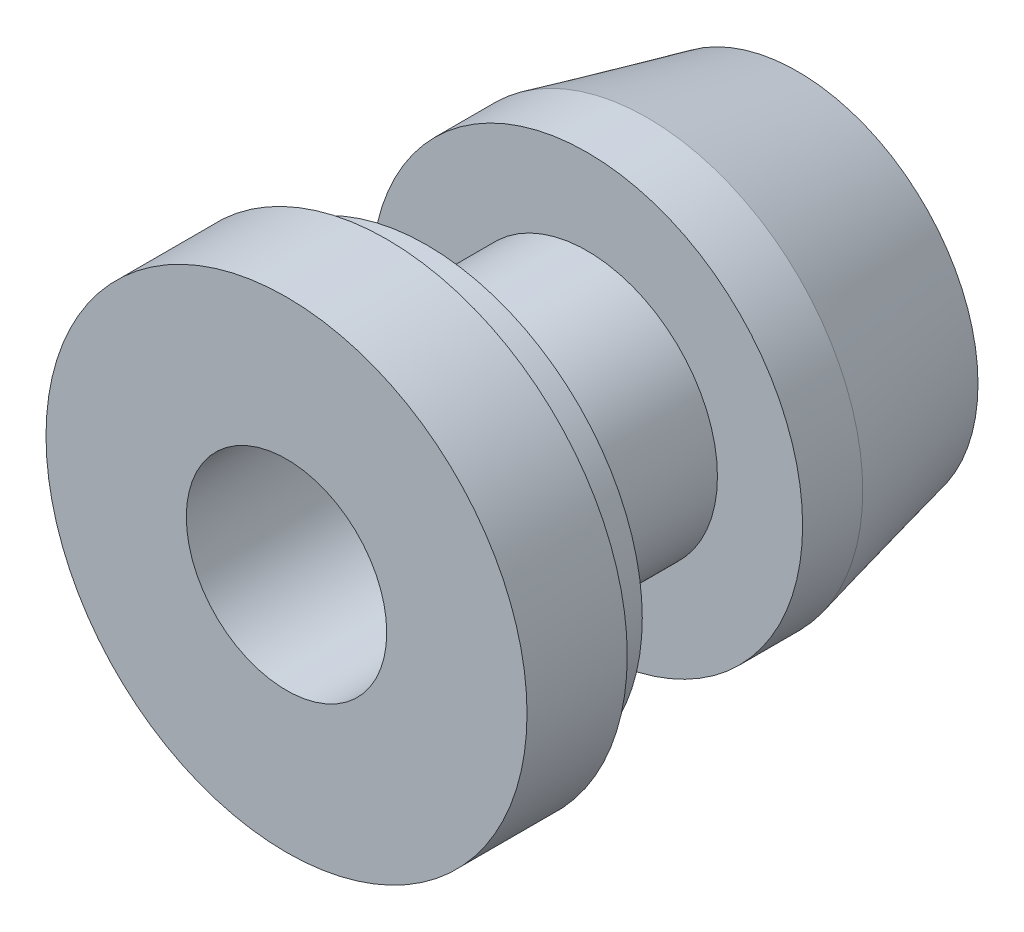
SolidWorks part; units mm, degrees
ref_plane "Plan de face" through (0, 0, 0) normal (0, 0, 1) x (1, 0, 0)
ref_plane "Plan de dessus" through (0, 0, 0) normal (0, 1, 0) x (1, 0, 0)
ref_plane "Plan de droite" through (0, 0, 0) normal (1, 0, 0) x (0, 0, -1)
sketch "Esquisse1" plane through (0, 0, 0) normal (0, 0, 1) x (1, 0, 0)
  circle A0 centre (0, 0) radius 4.3
  circle A1 centre (0, 0) radius 2.6
  circle A2 centre (0, 0) radius 2
  dimension "D1" = 8.6
  dimension "D2" = 5.2
  dimension "D3" = 4
extrude "Boss.-Extru.1" add sketch "Esquisse1" along normal blind 1.2 contours A0 A1 | A1 A2
sketch "Esquisse2" plane through (0, 0, 1.2) normal (0, 0, 1) x (1, 0, 0)
  circle A0 centre (0, 0) radius 2.6
  circle A1 centre (0, 0) radius 2
  dimension "D1" = 5.2
extrude "Boss.-Extru.3" add sketch "Esquisse2" along normal blind 3.2
sketch "Esquisse3" plane through (0, 0, 4.4) normal (0, 0, 1) x (1, 0, 0)
  circle A0 centre (0, 0) radius 2
  circle A1 centre (0, 0) radius 4.3
extrude "Boss.-Extru.4" add sketch "Esquisse3" along normal blind 0.8
sketch "Esquisse4" plane through (0, 0, 5.2) normal (0, 0, 1) x (1, 0, 0)
  circle A0 centre (0, 0) radius 2
  circle A1 centre (0, 0) radius 4.8
  dimension "D1" = 9.6
extrude "Boss.-Extru.5" add sketch "Esquisse4" along normal blind 2
sketch "Esquisse5" plane through (0, 0, 0) normal (0, 1, 0) x (1, 0, 0)
  line L0 (0, -7.3163) -> (0, 2.9947) construction
  line L1 (-4.3, 0) -> (-3.6, 3)
  line L2 (-3.6, 3) -> (0, 2.9947)
  line L3 (0, 2.9947) -> (0, 0)
  line L4 (0, 0) -> (-4.3, 0)
  dimension "D1" = 3.6
  dimension "D2" = 4.3
  dimension "D3" = 3
sketch "Esquisse6" plane through (0, 0, 0) normal (0, 0, -1) x (-1, 0, 0)
  circle A0 centre (0, 0) radius 3
  dimension "D1" = 6
revolve "Révolution2" add sketch "Esquisse5" angle 360 about L0
extrude "Enlèv. mat.-Extru.1" cut sketch "Esquisse6" along normal blind 3
